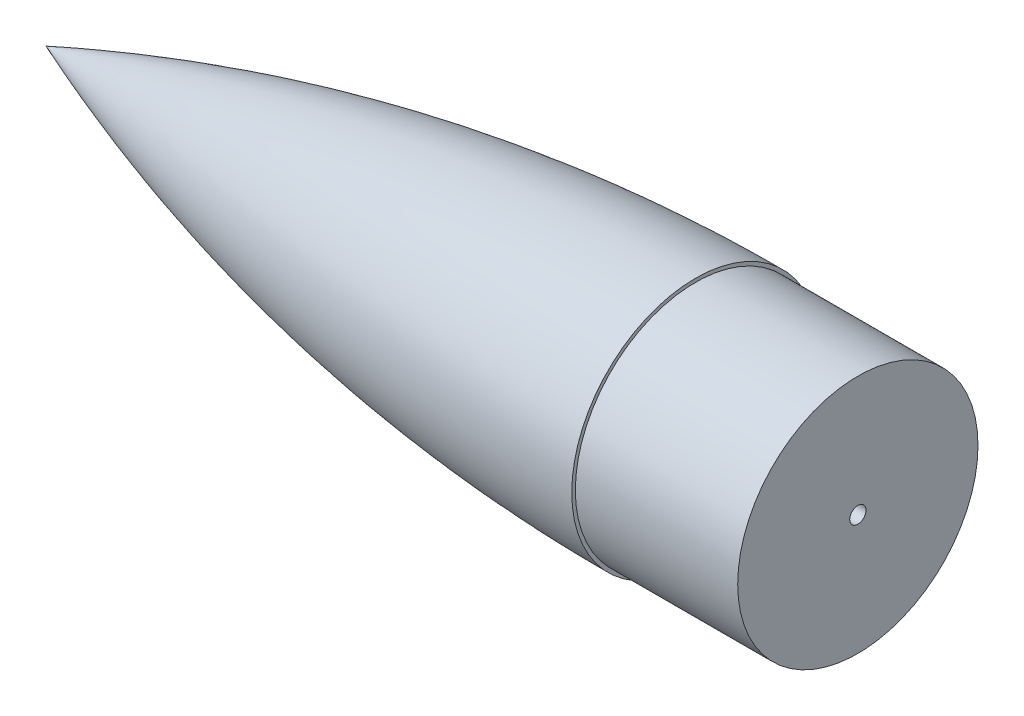
SolidWorks part; units mm, degrees
ref_plane "Front Plane" through (0, 0, 0) normal (0, 0, 1) x (1, 0, 0)
ref_plane "Top Plane" through (0, 0, 0) normal (0, 1, 0) x (1, 0, 0)
ref_plane "Right Plane" through (0, 0, 0) normal (1, 0, 0) x (0, 0, -1)
curve "Curve1"
  spline degree 3 poles (0, 0, 0) (0.3333, 0.1315, 0) (0.9996, 0.3945, 0) (1.9996, 0.7863, 0) (2.9996, 1.176, 0) (3.9996, 1.5634, 0) (4.9996, 1.9485, 0) (5.9996, 2.3314, 0) (6.9996, 2.712, 0) (7.9996, 3.0903, 0) (8.9996, 3.4664, 0) (9.9996, 3.8403, 0) (10.9996, 4.2119, 0) (11.9996, 4.5813, 0) (12.9996, 4.9485, 0) (13.9996, 5.3135, 0) (14.9996, 5.6762, 0) (15.9996, 6.0368, 0) (16.9997, 6.3951, 0) (17.9997, 6.7512, 0) (18.9997, 7.1051, 0) (19.9997, 7.4569, 0) (20.9997, 7.8064, 0) (21.9997, 8.1538, 0) (22.9997, 8.499, 0) (23.9997, 8.842, 0) (24.9997, 9.1829, 0) (25.9997, 9.5215, 0) (26.9997, 9.8581, 0) (27.9997, 10.1924, 0) (28.9997, 10.5246, 0) (29.9997, 10.8547, 0) (30.9997, 11.1826, 0) (31.9997, 11.5084, 0) (32.9997, 11.832, 0) (33.9997, 12.1535, 0) (34.9997, 12.4729, 0) (35.9997, 12.7902, 0) (36.9997, 13.1053, 0) (37.9997, 13.4183, 0) (38.9997, 13.7292, 0) (39.9997, 14.038, 0) (40.9997, 14.3447, 0) (41.9997, 14.6493, 0) (42.9997, 14.9518, 0) (43.9997, 15.2521, 0) (44.9997, 15.5504, 0) (45.9997, 15.8467, 0) (46.9997, 16.1408, 0) (47.9997, 16.4328, 0) (48.9997, 16.7228, 0) (49.9997, 17.0107, 0) (50.9997, 17.2966, 0) (51.9997, 17.5803, 0) (52.9997, 17.862, 0) (53.9997, 18.1417, 0) (54.9997, 18.4192, 0) (55.9997, 18.6948, 0) (56.9997, 18.9683, 0) (57.9997, 19.2397, 0) (58.9997, 19.5091, 0) (59.9997, 19.7764, 0) (60.9997, 20.0417, 0) (61.9998, 20.305, 0) (62.9998, 20.5663, 0) (63.9998, 20.8255, 0) (64.9998, 21.0827, 0) (65.9998, 21.3379, 0) (66.9998, 21.591, 0) (67.9998, 21.8422, 0) (68.9998, 22.0913, 0) (69.9998, 22.3384, 0) (70.9998, 22.5835, 0) (71.9998, 22.8266, 0) (72.9998, 23.0677, 0) (73.9998, 23.3068, 0) (74.9998, 23.5439, 0) (75.9998, 23.779, 0) (76.9998, 24.0121, 0) (77.9998, 24.2433, 0) (78.9998, 24.4724, 0) (79.9998, 24.6995, 0) (80.9998, 24.9247, 0) (81.9998, 25.1479, 0) (82.9998, 25.3691, 0) (83.9998, 25.5884, 0) (84.9998, 25.8057, 0) (85.9998, 26.021, 0) (86.9998, 26.2343, 0) (87.9998, 26.4457, 0) (88.9998, 26.6551, 0) (89.9998, 26.8626, 0) (90.9998, 27.0681, 0) (91.9998, 27.2716, 0) (92.9998, 27.4732, 0) (93.9998, 27.6728, 0) (94.9998, 27.8705, 0) (95.9998, 28.0663, 0) (96.9998, 28.2601, 0) (97.9998, 28.452, 0) (98.9998, 28.6419, 0) (99.9998, 28.8299, 0) (100.9998, 29.0159, 0) (101.9998, 29.2, 0) (102.9998, 29.3822, 0) (103.9998, 29.5625, 0) (104.9998, 29.7408, 0) (105.9998, 29.9172, 0) (106.9998, 30.0917, 0) (107.9998, 30.2642, 0) (108.9998, 30.4349, 0) (109.9998, 30.6036, 0) (110.9998, 30.7704, 0) (111.9998, 30.9353, 0) (112.9998, 31.0982, 0) (113.9999, 31.2593, 0) (114.9999, 31.4184, 0) (115.9999, 31.5757, 0) (116.9999, 31.731, 0) (117.9999, 31.8845, 0) (118.9999, 32.036, 0) (119.9999, 32.1856, 0) (120.9999, 32.3333, 0) (121.9999, 32.4792, 0) (122.9999, 32.6231, 0) (123.9999, 32.7652, 0) (124.9999, 32.9053, 0) (125.9999, 33.0436, 0) (126.9999, 33.1799, 0) (127.9999, 33.3144, 0) (128.9999, 33.447, 0) (129.9999, 33.5777, 0) (130.9999, 33.7065, 0) (131.9999, 33.8334, 0) (132.9999, 33.9585, 0) (133.9999, 34.0817, 0) (134.9999, 34.203, 0) (135.9999, 34.3224, 0) (136.9999, 34.4399, 0) (137.9999, 34.5556, 0) (138.9999, 34.6693, 0) (139.9999, 34.7813, 0) (140.9999, 34.8913, 0) (141.9999, 34.9995, 0) (142.9999, 35.1058, 0) (143.9999, 35.2102, 0) (144.9999, 35.3127, 0) (145.9999, 35.4134, 0) (146.9999, 35.5123, 0) (147.9999, 35.6092, 0) (148.9999, 35.7043, 0) (149.9999, 35.7976, 0) (150.9999, 35.8889, 0) (151.9999, 35.9785, 0) (152.9999, 36.0661, 0) (153.9999, 36.1519, 0) (154.9999, 36.2358, 0) (155.9999, 36.3179, 0) (156.9999, 36.3981, 0) (157.9999, 36.4765, 0) (158.9999, 36.553, 0) (159.9999, 36.6277, 0) (160.9999, 36.7005, 0) (161.9999, 36.7714, 0) (162.9999, 36.8405, 0) (163.9999, 36.9078, 0) (164.9999, 36.9732, 0) (165.9999, 37.0367, 0) (166.9999, 37.0984, 0) (167.9999, 37.1583, 0) (168.9999, 37.2163, 0) (169.9999, 37.2724, 0) (171, 37.3268, 0) (172, 37.3792, 0) (173, 37.4298, 0) (174, 37.4786, 0) (175, 37.5255, 0) (176, 37.5706, 0) (177, 37.6139, 0) (178, 37.6553, 0) (179, 37.6948, 0) (180, 37.7325, 0) (181, 37.7684, 0) (182, 37.8024, 0) (183, 37.8346, 0) (184, 37.865, 0) (185, 37.8935, 0) (186, 37.9201, 0) (187, 37.9449, 0) (188, 37.9679, 0) (189, 37.9891, 0) (190, 38.0084, 0) (191, 38.0258, 0) (192, 38.0415, 0) (193, 38.0553, 0) (194, 38.0672, 0) (195, 38.0773, 0) (196, 38.0856, 0) (197, 38.092, 0) (198, 38.0966, 0) (199, 38.0995, 0) (199.6667, 38.0998, 0) (200, 38.1, 0) knots 0 0 0 0 0.005248 0.010493 0.015733 0.020969 0.026202 0.03143 0.036654 0.041875 0.047091 0.052304 0.057513 0.062718 0.06792 0.073118 0.078312 0.083502 0.088689 0.093872 0.099051 0.104227 0.1094 0.114569 0.119734 0.124896 0.130055 0.13521 0.140362 0.14551 0.150655 0.155797 0.160935 0.166071 0.171203 0.176332 0.181457 0.18658 0.191699 0.196816 0.201929 0.207039 0.212146 0.21725 0.222352 0.22745 0.232545 0.237638 0.242727 0.247814 0.252898 0.257979 0.263057 0.268133 0.273205 0.278275 0.283343 0.288407 0.293469 0.298529 0.303586 0.30864 0.313691 0.31874 0.323787 0.328831 0.333873 0.338912 0.343949 0.348983 0.354015 0.359045 0.364072 0.369097 0.374119 0.37914 0.384158 0.389174 0.394187 0.399199 0.404208 0.409215 0.41422 0.419223 0.424224 0.429222 0.434219 0.439214 0.444206 0.449197 0.454185 0.459172 0.464157 0.46914 0.474121 0.4791 0.484077 0.489052 0.494026 0.498998 0.503968 0.508936 0.513902 0.518867 0.52383 0.528792 0.533751 0.538709 0.543666 0.548621 0.553574 0.558526 0.563476 0.568425 0.573372 0.578317 0.583262 0.588204 0.593146 0.598085 0.603024 0.607961 0.612897 0.617831 0.622764 0.627696 0.632626 0.637555 0.642483 0.64741 0.652335 0.65726 0.662183 0.667105 0.672025 0.676945 0.681863 0.686781 0.691697 0.696612 0.701527 0.70644 0.711352 0.716263 0.721173 0.726083 0.730991 0.735898 0.740805 0.745711 0.750615 0.755519 0.760422 0.765325 0.770226 0.775127 0.780026 0.784926 0.789824 0.794722 0.799619 0.804515 0.809411 0.814306 0.8192 0.824094 0.828987 0.833879 0.838771 0.843663 0.848554 0.853444 0.858334 0.863224 0.868113 0.873001 0.877889 0.882777 0.887664 0.892551 0.897438 0.902324 0.90721 0.912095 0.91698 0.921865 0.92675 0.931634 0.936519 0.941403 0.946286 0.95117 0.956054 0.960937 0.96582 0.970703 0.975586 0.980469 0.985352 0.990235 0.995117 1 1 1 1
ref_plane "Plane2" through (0, 0, 0) normal (0, 0, 1) x (1, 0, 0)
sketch "Sketch3" plane through (0, 0, 0) normal (0, 0, 1) x (1, 0, 0)
  line L0 (0, 0) -> (200, 0)
  line L1 (200, 0) -> (200, 38.1)
  spline S2 degree 3 poles (-892.8612, 1786.5752) (-104.7306, -54.3565) (-53.804, -21.0773) (1.9996, 0.7863) (2.9996, 1.176) (4.665, 1.8211) (7.3287, 2.841) (11.326, 4.3399) (15.3276, 5.8003) (21.6484, 8.0514) (32.5949, 11.7827) (44.6178, 15.4959) (54.6586, 18.3348) (59.9937, 19.783) (64.3293, 20.9157) (68.6628, 22.0127) (73.9903, 23.3185) (78.994, 24.48) (83.9973, 25.5918) (87.3301, 26.3094) (93.3247, 27.553) (99.9872, 28.8507) (109.6522, 30.5743) (118.3203, 31.9622) (124.9975, 32.9107) (132.9895, 33.9854) (141.3183, 34.9722) (150.6635, 35.8697) (156.9977, 36.4072) (166.9899, 37.1533) (176.661, 37.6429) (186.3327, 37.9364) (190.6663, 38.028) (194.3333, 38.0718) (196, 38.0856) (197, 38.092) (198, 38.0966) (256.4455, 38.2639) (314.5749, 26.6134) (369.4491, 2028.2244) knots -0.862185 -0.862185 -0.862185 -0.862185 0.005248 0.010493 0.015733 0.020969 0.036654 0.057513 0.083502 0.099051 0.155797 0.252898 0.283343 0.30864 0.333873 0.348983 0.374119 0.41422 0.424224 0.449197 0.464157 0.513902 0.548621 0.607961 0.642483 0.64741 0.726083 0.765325 0.784926 0.8192 0.912095 0.92675 0.960937 0.975586 0.980469 0.985352 0.990235 0.995117 1.841473 1.841473 1.841473 1.841473 only from (0, 0) to (200, 38.1) construction
  spline S3 degree 3 poles (0, 0) (0.3333, 0.1315) (0.9996, 0.3945) (1.9996, 0.7863) (2.9996, 1.176) (4.665, 1.8211) (7.3287, 2.841) (11.326, 4.3399) (15.3276, 5.8003) (21.6484, 8.0514) (32.5949, 11.7827) (44.6178, 15.4959) (54.6586, 18.3348) (59.9937, 19.783) (64.3293, 20.9157) (68.6628, 22.0127) (73.9903, 23.3185) (78.994, 24.48) (83.9973, 25.5918) (87.3301, 26.3094) (93.3247, 27.553) (99.9872, 28.8507) (109.6522, 30.5743) (118.3203, 31.9622) (124.9975, 32.9107) (132.9895, 33.9854) (141.3183, 34.9722) (150.6635, 35.8697) (156.9977, 36.4072) (166.9899, 37.1533) (176.661, 37.6429) (186.3327, 37.9364) (190.6663, 38.028) (194.3333, 38.0718) (196, 38.0856) (197, 38.092) (198, 38.0966) (199, 38.0995) (199.6667, 38.0998) (200, 38.1) knots 0 0 0 0 0.005248 0.010493 0.015733 0.020969 0.036654 0.057513 0.083502 0.099051 0.155797 0.252898 0.283343 0.30864 0.333873 0.348983 0.374119 0.41422 0.424224 0.449197 0.464157 0.513902 0.548621 0.607961 0.642483 0.64741 0.726083 0.765325 0.784926 0.8192 0.912095 0.92675 0.960937 0.975586 0.980469 0.985352 0.990235 0.995117 1 1 1 1
revolve "Revolve1" add sketch "Sketch3" angle 360 about L0
sketch "Sketch10" plane through (200, 0, 0) normal (1, 0, 0) x (0, 0, -1)
  circle A6 centre (0, 0) radius 37
  dimension "D1" = 74
extrude "Boss-Extrude1" add sketch "Sketch10" along normal blind 50
sketch "Sketch11" plane through (250, 0, 0) normal (1, 0, 0) x (0, 0, -1)
  circle A0 centre (0, 0) radius 2.5
  dimension "D1" = 5
extrude "Cut-Extrude1" cut sketch "Sketch11" against normal blind 25
